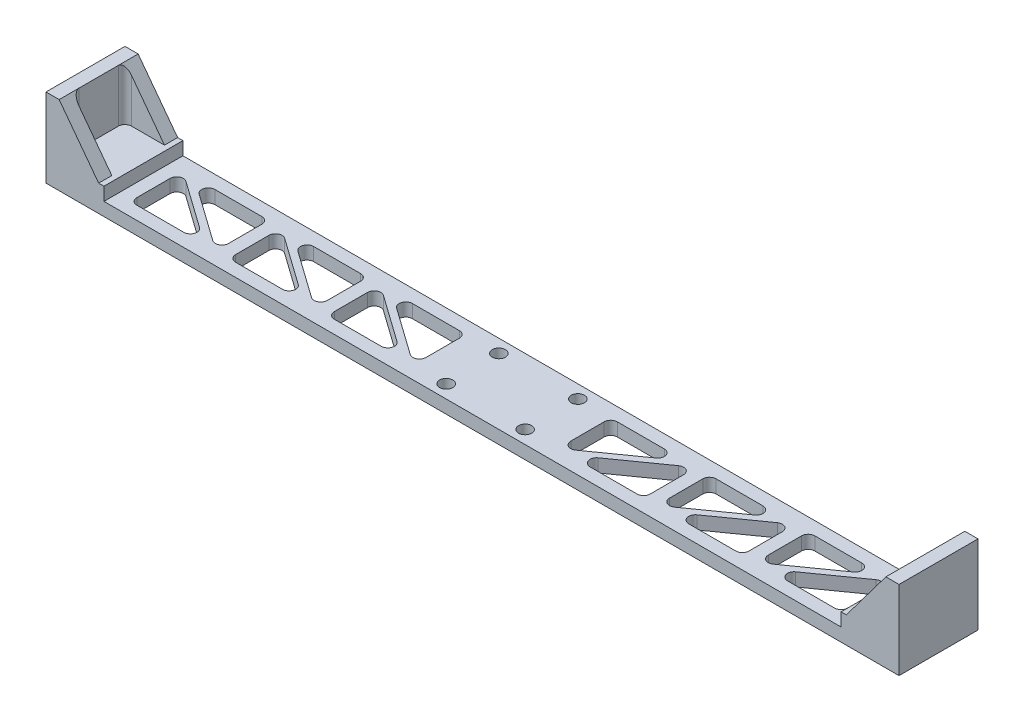
SolidWorks part; units mm, degrees
ref_plane "Front Plane" through (0, 0, 0) normal (0, 0, 1) x (1, 0, 0)
ref_plane "Top Plane" through (0, 0, 0) normal (0, 1, 0) x (1, 0, 0)
ref_plane "Right Plane" through (0, 0, 0) normal (1, 0, 0) x (0, 0, -1)
sketch "Sketch1" plane through (0, 0, 0) normal (1, 0, 0) x (0, 0, -1)
  line L1 (-19.05, 19.05) -> (19.05, 19.05)
  line L2 (-19.05, 19.05) -> (-19.05, -19.05)
  line L3 (-19.05, -19.05) -> (19.05, -19.05)
  line L4 (19.05, 19.05) -> (19.05, -19.05)
  line L5 (-19.05, 19.05) -> (19.05, -19.05) construction
  line L6 (-19.05, -19.05) -> (19.05, 19.05) construction
  point P0 (0, 0)
  dimension "D1" = 38.1
extrude "Boss-Extrude1" add sketch "Sketch1" along normal mid plane 411.48
sketch "Sketch3" plane through (0, 0, 19.05) normal (0, 0, 1) x (1, 0, 0)
  line L0 (-199.39, 19.05) -> (-180.34, -6.35)
  line L1 (205.74, 19.05) -> (-205.74, 19.05) construction
  line L2 (-180.34, -6.35) -> (180.34, -6.35)
  line L3 (-205.74, 19.05) -> (-205.74, -19.05) construction
  line L4 (205.74, -19.05) -> (-205.74, -19.05) construction
  line L5 (-199.39, 19.05) -> (199.39, 19.05)
  line L6 (0, 19.05) -> (0, -6.35) construction
  line L7 (199.39, 19.05) -> (180.34, -6.35)
  dimension "D1" = 6.35
  dimension "D2" = 25.4
  dimension "D3" = 12.7
extrude "Cut-Extrude1" cut sketch "Sketch3" against normal up to next
sketch "Sketch4" plane through (0, 19.05, 0) normal (0, 1, 0) x (1, 0, 0)
  line L0 (-199.39, 9.525) -> (-199.39, -9.525)
  line L1 (-199.39, 19.05) -> (-199.39, -19.05) construction
  line L2 (-196.215, -12.7) -> (-148.59, -12.7)
  line L3 (-148.59, -12.7) -> (-148.59, 12.7)
  line L4 (-148.59, 12.7) -> (-196.215, 12.7)
  line L5 (-205.74, 0) -> (0, 0) construction
  line L6 (-205.74, 19.05) -> (-205.74, -19.05) construction
  line L7 (-180.34, 19.05) -> (-199.39, 19.05) construction
  line L8 (0, 0) -> (0, -19.05) construction
  line L9 (-180.34, -19.05) -> (180.34, -19.05) construction
  line L10 (148.59, 12.7) -> (196.215, 12.7)
  line L11 (148.59, -12.7) -> (148.59, 12.7)
  line L12 (196.215, -12.7) -> (148.59, -12.7)
  line L13 (199.39, 9.525) -> (199.39, -9.525)
  arc A0 (-199.39, -9.525) -> (-196.215, -12.7) centre (-196.215, -9.525) ccw
  arc A1 (-199.39, 9.525) -> (-196.215, 12.7) centre (-196.215, 9.525) cw
  arc A2 (199.39, 9.525) -> (196.215, 12.7) centre (196.215, 9.525) ccw
  arc A3 (199.39, -9.525) -> (196.215, -12.7) centre (196.215, -9.525) cw
  point P11 (-199.39, 0)
  point P16 (-199.39, -12.7)
  point P19 (-199.39, 12.7)
  point P31 (199.39, 12.7)
  point P32 (199.39, -12.7)
  dimension "D3" = 3.175
  dimension "D1" = 6.35
  dimension "D2" = 50.8
extrude "Cut-Extrude2" cut sketch "Sketch4" against normal up to surface (25.4 mm away) contours L4 A1 L0 A0 L2 L3
hole_wizard "1/4 (0.25) Diameter Hole1" positions "Sketch8" profile "Sketch9" hole size "1/4" standard "ANSI Inch" end condition up to next
sketch "Sketch8" plane through (0, -6.35, 0) normal (0, 1, 0) x (1, 0, 0)
  line L1 (-19.05, 12.7) -> (19.05, 12.7) construction
  line L2 (-19.05, 12.7) -> (-19.05, -12.7) construction
  line L3 (-19.05, -12.7) -> (19.05, -12.7) construction
  line L4 (19.05, 12.7) -> (19.05, -12.7) construction
  line L5 (-19.05, 12.7) -> (19.05, -12.7) construction
  line L6 (-19.05, -12.7) -> (19.05, 12.7) construction
  point P2 (19.05, -12.7)
  point P77 (-19.05, 12.7)
  point P78 (-19.05, -12.7)
  point P79 (19.05, 12.7)
  point P82 (0, 0)
  dimension "D1" = 38.1
  dimension "D2" = 25.4
sketch "Sketch9" plane through (19.05, -6.35, 12.7) normal (1, 0, 0) x (0, 0, 1)
  line L0 (0, 0) -> (0, 12.7)
  line L1 (0, 12.7) -> (3.175, 12.7)
  line L2 (3.175, 12.7) -> (3.175, 0)
  line L5 (3.175, 0) -> (0, 0)
  line L11 (0, -6.35) -> (0, 107.95) construction
  dimension "Thru Hole Dia." = 6.35
  dimension "Thru Hole Depth" = 12.7
sketch "Sketch10" plane through (0, -6.35, 0) normal (0, 1, 0) x (1, 0, 0)
  line L0 (180.34, 19.05) -> (-180.34, 19.05) construction
  line L1 (-177.8, 19.05) -> (177.8, 19.05)
  line L2 (-177.8, 19.05) -> (-177.8, -19.05)
  line L3 (-177.8, -19.05) -> (177.8, -19.05)
  line L4 (177.8, 19.05) -> (177.8, -19.05)
  line L5 (-180.34, -19.05) -> (180.34, -19.05) construction
  point P8 (0, 19.05)
  dimension "D1" = 355.6
extrude "Cut-Extrude3" cut sketch "Sketch10" against normal blind 6.35
sketch "Sketch11" plane through (0, -12.7, 0) normal (0, 1, 0) x (1, 0, 0)
  line L0 (-171.45, 12.7) -> (-171.45, -12.7)
  line L1 (-171.45, -12.7) -> (-135.6608, -12.7)
  line L2 (-135.6608, -12.7) -> (-171.45, 12.7)
  line L3 (-165.9642, 12.7) -> (-130.175, -12.7)
  line L4 (-130.175, -12.7) -> (-130.175, 12.7)
  line L5 (-130.175, 12.7) -> (-165.9642, 12.7)
  line L6 (-153.5554, 0) -> (-151.7178, 2.5892) construction
  line L7 (-171.45, 0) -> (-177.8, 0) construction
  line L8 (-177.8, 19.05) -> (-177.8, -19.05) construction
  line L11 (-130.175, 0) -> (-123.825, 0) construction
  line L12 (-123.825, 12.7) -> (-123.825, -12.7)
  line L13 (-123.825, -12.7) -> (-88.0358, -12.7)
  line L14 (-88.0358, -12.7) -> (-123.825, 12.7)
  line L15 (-118.3392, 12.7) -> (-82.55, -12.7)
  line L16 (-82.55, -12.7) -> (-82.55, 12.7)
  line L17 (-82.55, 12.7) -> (-118.3392, 12.7)
  line L18 (-105.9304, 0) -> (-104.0928, 2.5892) construction
  line L19 (-82.55, 0) -> (-76.2, 0) construction
  line L20 (-76.2, 12.7) -> (-76.2, -12.7)
  line L21 (-76.2, -12.7) -> (-40.4108, -12.7)
  line L22 (-40.4108, -12.7) -> (-76.2, 12.7)
  line L23 (-70.7142, 12.7) -> (-34.925, -12.7)
  line L24 (-34.925, -12.7) -> (-34.925, 12.7)
  line L25 (-34.925, 12.7) -> (-70.7142, 12.7)
  line L26 (-58.3054, 0) -> (-56.4678, 2.5892) construction
  line L28 (-34.925, 0) -> (-28.575, 0) construction
  line L29 (177.8, 19.05) -> (-177.8, 19.05) construction
  line L30 (-28.575, 19.05) -> (-28.575, -19.05) construction
  line L31 (-177.8, -19.05) -> (177.8, -19.05) construction
  dimension "D1" = 3
  dimension "D2" = 6.35
  dimension "D3" = 6.35
  dimension "D4" = 28.575
  dimension "D5" = 3.175
extrude "Cut-Extrude4" cut sketch "Sketch11" against normal up to next
fillet "Fillet1" radius 3.175 18 edges at (-34.925, -15.875, -12.7) (-34.925, -15.875, 12.7) (-70.7142, -15.875, -12.7) (-40.4108, -15.875, 12.7) (-76.2, -15.875, 12.7) (-76.2, -15.875, -12.7) (-82.55, -15.875, -12.7) (-118.3392, -15.875, -12.7) (-82.55, -15.875, 12.7) (-88.0358, -15.875, 12.7) (-123.825, -15.875, 12.7) (-123.825, -15.875, -12.7) (-130.175, -15.875, -12.7) (-130.175, -15.875, 12.7) (-165.9642, -15.875, -12.7) (-135.6608, -15.875, 12.7) (-171.45, -15.875, 12.7) (-171.45, -15.875, -12.7)
mirror "Mirror1" about plane through (0, 0, 0) normal (1, 0, 0) of "Cut-Extrude4", "Fillet1"
